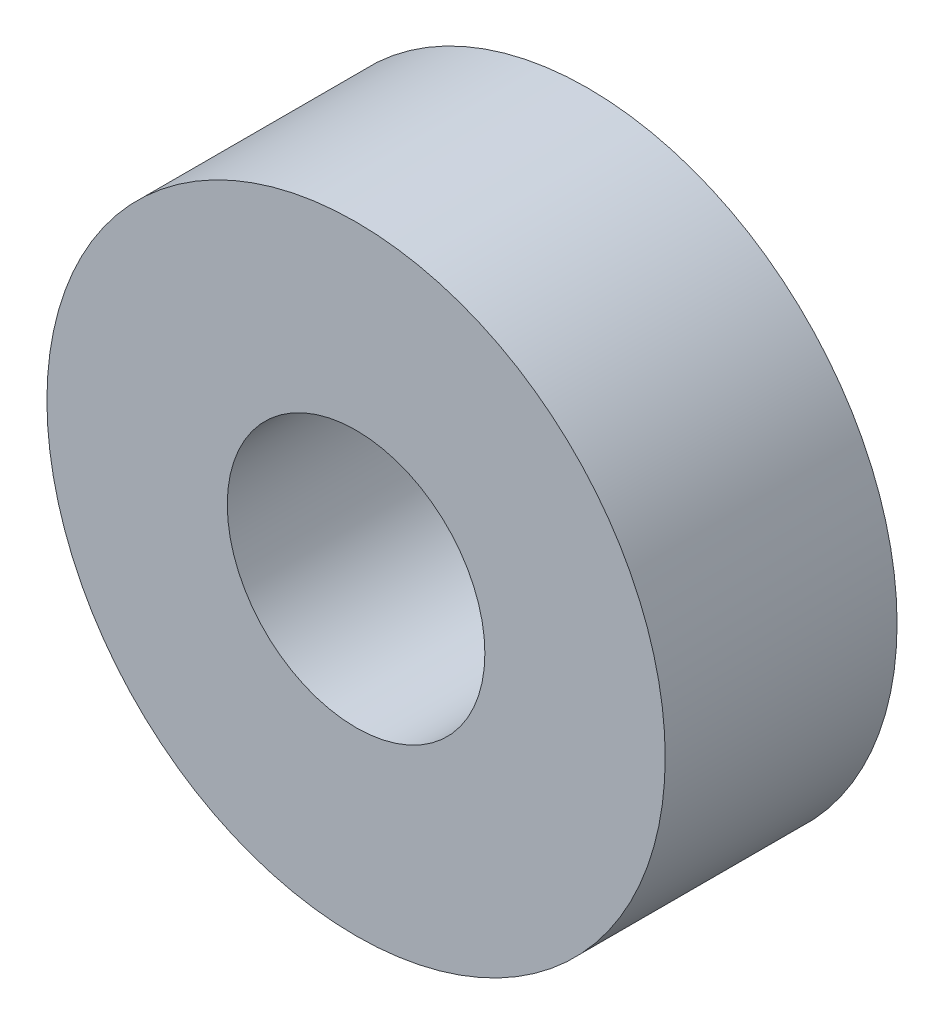
SolidWorks part; units mm, degrees
ref_plane "Płaszczyzna przednia" through (0, 0, 0) normal (0, 0, 1) x (1, 0, 0)
ref_plane "Płaszczyzna górna" through (0, 0, 0) normal (0, 1, 0) x (1, 0, 0)
ref_plane "Płaszczyzna prawa" through (0, 0, 0) normal (1, 0, 0) x (0, 0, -1)
sketch "Szkic1" plane through (0, 0, 0) normal (0, 0, 1) x (1, 0, 0)
  circle A0 centre (521.3796, -27.9028) radius 12
  circle A1 centre (521.3796, -27.9028) radius 5
  dimension "D1" = 24
  dimension "D2" = 10
extrude "Dodanie-wyciągnięcie1" add sketch "Szkic1" along normal blind 9
